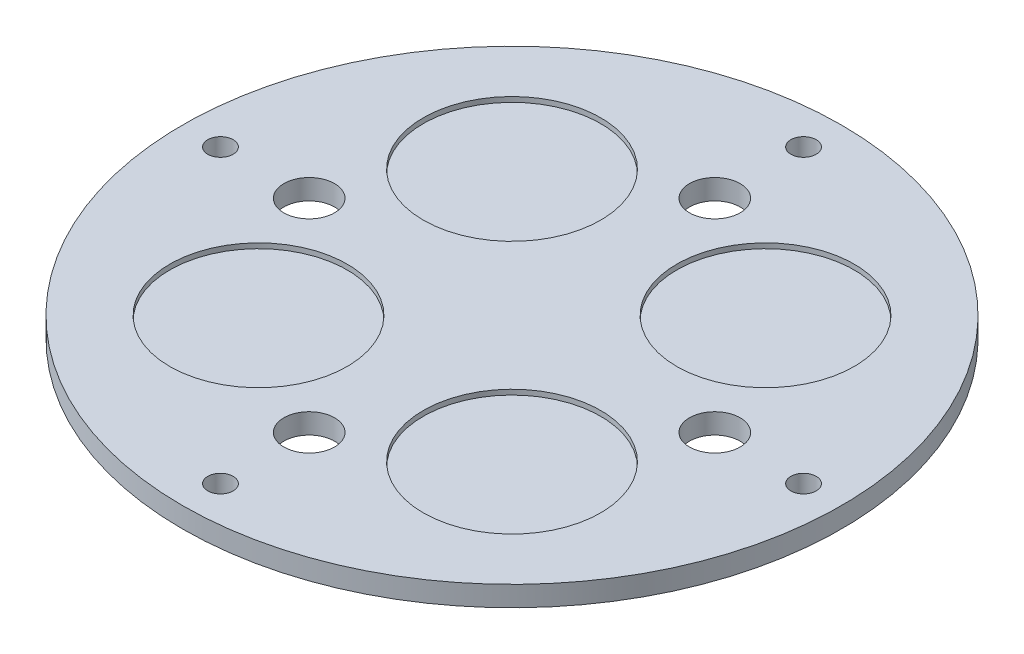
SolidWorks part; units mm, degrees
ref_plane "Front Plane" through (0, 0, 0) normal (0, 0, 1) x (1, 0, 0)
ref_plane "Top Plane" through (0, 0, 0) normal (0, 1, 0) x (1, 0, 0)
ref_plane "Right Plane" through (0, 0, 0) normal (1, 0, 0) x (0, 0, -1)
sketch "Sketch1" plane through (0, 0, 0) normal (0, 1, 0) x (1, 0, 0)
  circle A0 centre (0, 0) radius 17.5
  circle A1 centre (50, 0) radius 17.5
  circle A2 centre (50, -50) radius 17.5
  circle A3 centre (0, -50) radius 17.5
  circle A5 centre (25, -25) radius 65
  dimension "D1" = 35
  dimension "D4" = 130
  dimension "D2" = 50
  dimension "D3" = 50
extrude "Boss-Extrude2" add sketch "Sketch1" along normal blind 1
sketch "Sketch2" plane through (0, 0, 0) normal (0, -1, 0) x (1, 0, 0)
  circle A0 centre (25, 25) radius 65
  circle A1 centre (25, 25) radius 65 construction
extrude "Boss-Extrude3" add sketch "Sketch2" along normal blind 3
sketch "Sketch3" plane through (0, 1, 0) normal (0, 1, 0) x (1, 0, 0)
  circle A2 centre (25, 15) radius 5
  circle A3 centre (65, -25) radius 5
  circle A4 centre (25, -65) radius 5
  circle A5 centre (-15, -25) radius 5
  point P11 (25, -25)
  dimension "D1" = 4
  dimension "1" = 10
extrude "Cut-Extrude1" cut sketch "Sketch3" against normal through all
sketch "Sketch4" plane through (0, 1, 0) normal (0, 1, 0) x (1, 0, 0)
  circle A2 centre (25, 32.5) radius 2.5
  circle A3 centre (82.5, -25) radius 2.5
  circle A4 centre (25, -82.5) radius 2.5
  circle A5 centre (-32.5, -25) radius 2.5
  point P11 (25, -25)
  dimension "D1" = 4
  dimension "D2" = 5
extrude "Cut-Extrude2" cut sketch "Sketch4" against normal through all
